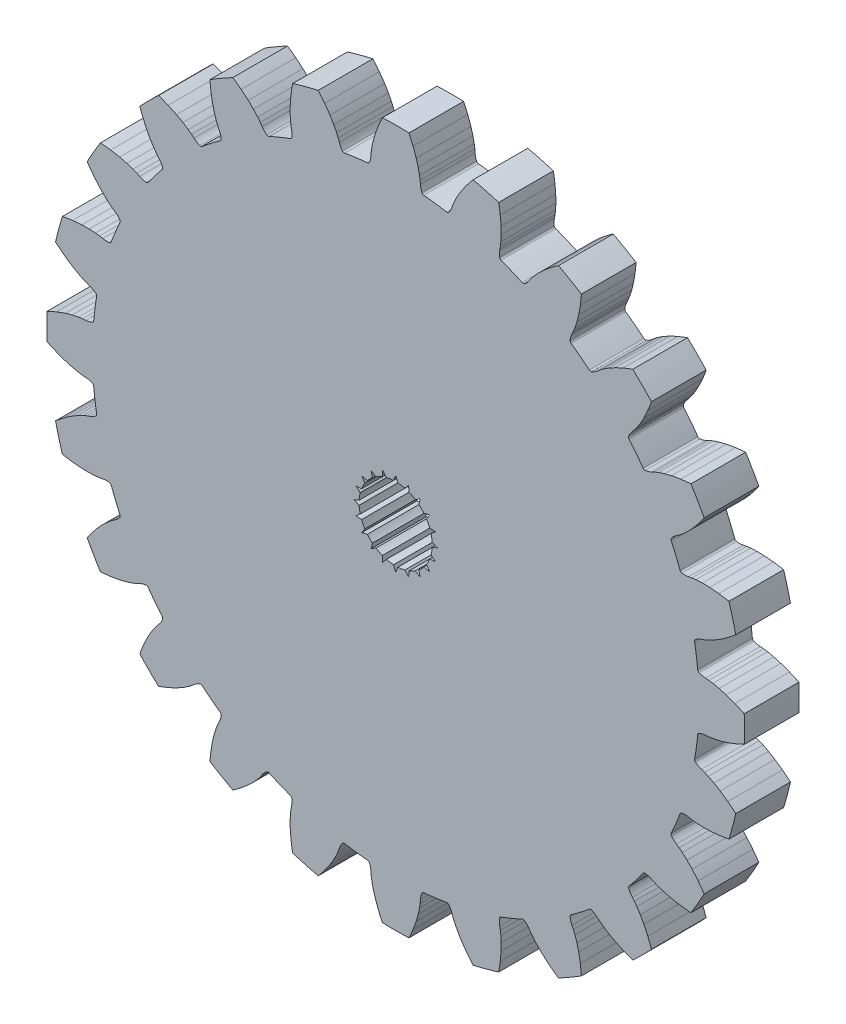
SolidWorks part; units mm, degrees
material "Cast Alloy Steel"
ref_plane "Front Plane" through (0, 0, 0) normal (0, 0, 1) x (1, 0, 0)
ref_plane "Top Plane" through (0, 0, 0) normal (0, 1, 0) x (1, 0, 0)
ref_plane "Right Plane" through (0, 0, 0) normal (1, 0, 0) x (0, 0, -1)
sketch "Model" plane through (0, 0, 0) normal (0, 0, 1) x (1, 0, 0)
  arc A1 (34.9181, -4.5971) -> (35.0673, -3.2696) centre (0, 0) ccw
  arc A2 (35.2278, -3.0481) -> (35.0673, -3.2696) centre (35.3347, -3.2945) ccw
  arc A3 (35.9833, -2.8721) -> (35.2278, -3.0481) centre (36.0877, -5.0299) ccw
  arc A4 (35.9833, -2.8721) -> (36.3636, -2.8405) centre (35.7172, 2.6237) ccw
  arc A5 (36.3636, -2.8405) -> (36.8336, -2.7716) centre (35.3622, 5.6245) ccw
  arc A6 (36.8336, -2.7716) -> (37.5555, -2.6174) centre (35.1043, 7.0963) ccw
  arc A7 (37.5555, -2.6174) -> (38.3737, -2.3829) centre (34.2966, 10.2971) ccw
  arc A8 (38.3737, -2.3829) -> (39.3866, -2.0164) centre (33.8084, 11.8154) ccw
  arc A9 (39.3866, -2.0164) -> (40.4752, -1.5354) centre (32.5769, 14.869) ccw
  arc A10 (40.4752, -1.5354) -> (40.4752, 1.5354) centre (0, 0) ccw
  arc A11 (40.4752, 1.5354) -> (39.3866, 2.0164) centre (32.5769, -14.869) ccw
  arc A12 (39.3866, 2.0164) -> (38.3737, 2.3829) centre (33.8084, -11.8154) ccw
  arc A13 (38.3737, 2.3829) -> (37.5555, 2.6174) centre (34.2966, -10.2971) ccw
  arc A14 (37.5555, 2.6174) -> (36.8336, 2.7716) centre (35.1043, -7.0963) ccw
  arc A15 (36.8336, 2.7716) -> (36.3636, 2.8405) centre (35.3622, -5.6245) ccw
  arc A16 (36.3636, 2.8405) -> (35.9833, 2.8721) centre (35.7172, -2.6237) ccw
  arc A17 (35.2278, 3.0481) -> (35.9833, 2.8721) centre (36.0877, 5.0299) ccw
  arc A18 (35.0673, 3.2696) -> (35.2278, 3.0481) centre (35.3347, 3.2945) ccw
  arc A19 (35.0673, 3.2696) -> (34.7187, 5.9179) centre (0, 0) ccw
  arc A20 (34.8164, 6.1734) -> (34.7187, 5.9179) centre (34.9834, 5.9631) ccw
  arc A21 (35.5005, 6.5389) -> (34.8164, 6.1734) centre (36.1599, 4.4817) ccw
  arc A22 (35.5005, 6.5389) -> (35.8597, 6.6679) centre (33.8211, 11.7785) ccw
  arc A23 (35.8597, 6.6679) -> (36.2958, 6.8561) centre (32.7015, 14.5853) ccw
  arc A24 (36.2958, 6.8561) -> (36.9533, 7.1918) centre (32.0715, 15.9402) ccw
  arc A25 (36.9533, 7.1918) -> (37.6829, 7.6301) centre (30.4629, 18.8229) ccw
  arc A26 (37.6829, 7.6301) -> (38.5664, 8.2463) centre (29.5984, 20.1631) ccw
  arc A27 (38.5664, 8.2463) -> (39.4934, 8.9927) centre (27.6185, 22.7939) ccw
  arc A28 (39.4934, 8.9927) -> (38.6987, 11.9589) centre (0, 0) ccw
  arc A29 (38.6987, 11.9589) -> (37.5227, 12.1417) centre (35.3153, -5.9309) ccw
  arc A30 (37.5227, 12.1417) -> (36.4494, 12.2336) centre (35.7145, -2.6625) ccw
  arc A31 (36.4494, 12.2336) -> (35.5984, 12.2483) centre (35.7931, -1.0696) ccw
  arc A32 (35.5984, 12.2483) -> (34.8612, 12.2104) centre (35.7448, 2.2311) ccw
  arc A33 (34.8612, 12.2104) -> (34.3894, 12.1553) centre (35.613, 3.7195) ccw
  arc A34 (34.3894, 12.1553) -> (34.0138, 12.0874) centre (35.1792, 6.71) ccw
  arc A35 (33.2386, 12.0619) -> (34.0138, 12.0874) centre (33.5562, 14.1987) ccw
  arc A36 (33.0262, 12.2343) -> (33.2386, 12.0619) centre (33.2781, 12.3275) ccw
  arc A37 (33.0262, 12.2343) -> (32.004, 14.7021) centre (0, 0) ccw
  arc A38 (32.0323, 14.9742) -> (32.004, 14.7021) centre (32.248, 14.8142) ccw
  arc A39 (32.5985, 15.5043) -> (32.0323, 14.9742) centre (33.7678, 13.6878) ccw
  arc A40 (32.5985, 15.5043) -> (32.912, 15.7219) centre (29.6202, 20.1308) ccw
  arc A41 (32.912, 15.7219) -> (33.2846, 16.0165) centre (27.8123, 22.5521) ccw
  arc A42 (33.2846, 16.0165) -> (33.8327, 16.511) centre (26.853, 23.6978) ccw
  arc A43 (33.8327, 16.511) -> (34.4241, 17.1232) centre (24.5532, 26.0659) ccw
  arc A44 (34.4241, 17.1232) -> (35.118, 17.9471) centre (23.3712, 27.1366) ccw
  arc A45 (35.118, 17.9471) -> (35.8203, 18.9079) centre (20.7779, 29.1654) ccw
  arc A46 (35.8203, 18.9079) -> (34.2849, 21.5673) centre (0, 0) ccw
  arc A47 (34.2849, 21.5673) -> (33.1016, 21.4395) centre (35.647, 3.4115) ccw
  arc A48 (33.1016, 21.4395) -> (32.0412, 21.2505) centre (35.1866, 6.6718) ccw
  arc A49 (32.0412, 21.2505) -> (31.2153, 21.0445) centre (34.8503, 8.2307) ccw
  arc A50 (31.2153, 21.0445) -> (30.513, 20.817) centre (33.9494, 11.4065) ccw
  arc A51 (30.513, 20.817) -> (30.0715, 20.6417) centre (33.4369, 12.8101) ccw
  arc A52 (30.0715, 20.6417) -> (29.7263, 20.479) centre (32.2438, 15.5865) ccw
  arc A53 (28.9841, 20.2537) -> (29.7263, 20.479) centre (28.7379, 22.3999) ccw
  arc A54 (28.7344, 20.3652) -> (28.9841, 20.2537) centre (28.9535, 20.5205) ccw
  arc A55 (28.7344, 20.3652) -> (27.1083, 22.4844) centre (0, 0) ccw
  arc A56 (27.0652, 22.7545) -> (27.1083, 22.4844) centre (27.315, 22.6559) ccw
  arc A57 (27.4749, 23.4131) -> (27.0652, 22.7545) centre (29.0746, 21.9612) ccw
  arc A58 (27.4749, 23.4131) -> (27.7215, 23.7044) centre (23.4007, 27.1111) ccw
  arc A59 (27.7215, 23.7044) -> (28.0051, 24.0855) centre (21.0277, 28.982) ccw
  arc A60 (28.0051, 24.0855) -> (28.4066, 24.7049) centre (19.8046, 29.8404) ccw
  arc A61 (28.4066, 24.7049) -> (28.8193, 25.4493) centre (16.9702, 31.5325) ccw
  arc A62 (28.8193, 25.4493) -> (29.2763, 26.4247) centre (15.5514, 32.2609) ccw
  arc A63 (29.2763, 26.4247) -> (29.706, 27.5346) centre (12.5214, 33.5494) ccw
  arc A64 (29.706, 27.5346) -> (27.5346, 29.706) centre (0, 0) ccw
  arc A65 (27.5346, 29.706) -> (26.4247, 29.2763) centre (33.5494, 12.5214) ccw
  arc A66 (26.4247, 29.2763) -> (25.4493, 28.8193) centre (32.2609, 15.5514) ccw
  arc A67 (25.4493, 28.8193) -> (24.7049, 28.4066) centre (31.5325, 16.9702) ccw
  arc A68 (24.7049, 28.4066) -> (24.0855, 28.0051) centre (29.8404, 19.8046) ccw
  arc A69 (24.0855, 28.0051) -> (23.7044, 27.7215) centre (28.982, 21.0277) ccw
  arc A70 (23.7044, 27.7215) -> (23.4131, 27.4749) centre (27.1111, 23.4007) ccw
  arc A71 (22.7545, 27.0652) -> (23.4131, 27.4749) centre (21.9612, 29.0746) ccw
  arc A72 (22.4844, 27.1083) -> (22.7545, 27.0652) centre (22.6559, 27.315) ccw
  arc A73 (22.4844, 27.1083) -> (20.3652, 28.7344) centre (0, 0) ccw
  arc A74 (20.2537, 28.9841) -> (20.3652, 28.7344) centre (20.5205, 28.9535) ccw
  arc A75 (20.479, 29.7263) -> (20.2537, 28.9841) centre (22.3999, 28.7379) ccw
  arc A76 (20.479, 29.7263) -> (20.6417, 30.0715) centre (15.5865, 32.2438) ccw
  arc A77 (20.6417, 30.0715) -> (20.817, 30.513) centre (12.8101, 33.4369) ccw
  arc A78 (20.817, 30.513) -> (21.0445, 31.2153) centre (11.4065, 33.9494) ccw
  arc A79 (21.0445, 31.2153) -> (21.2505, 32.0412) centre (8.2307, 34.8503) ccw
  arc A80 (21.2505, 32.0412) -> (21.4395, 33.1016) centre (6.6718, 35.1866) ccw
  arc A81 (21.4395, 33.1016) -> (21.5673, 34.2849) centre (3.4115, 35.647) ccw
  arc A82 (21.5673, 34.2849) -> (18.9079, 35.8203) centre (0, 0) ccw
  arc A83 (18.9079, 35.8203) -> (17.9471, 35.118) centre (29.1654, 20.7779) ccw
  arc A84 (17.9471, 35.118) -> (17.1232, 34.4241) centre (27.1366, 23.3712) ccw
  arc A85 (17.1232, 34.4241) -> (16.511, 33.8327) centre (26.0659, 24.5532) ccw
  arc A86 (16.511, 33.8327) -> (16.0165, 33.2846) centre (23.6978, 26.853) ccw
  arc A87 (16.0165, 33.2846) -> (15.7219, 32.912) centre (22.5521, 27.8123) ccw
  arc A88 (15.7219, 32.912) -> (15.5043, 32.5985) centre (20.1308, 29.6202) ccw
  arc A89 (14.9742, 32.0323) -> (15.5043, 32.5985) centre (13.6878, 33.7678) ccw
  arc A90 (14.7021, 32.004) -> (14.9742, 32.0323) centre (14.8142, 32.248) ccw
  arc A91 (14.7021, 32.004) -> (12.2343, 33.0262) centre (0, 0) ccw
  arc A92 (12.0619, 33.2386) -> (12.2343, 33.0262) centre (12.3275, 33.2781) ccw
  arc A93 (12.0874, 34.0138) -> (12.0619, 33.2386) centre (14.1987, 33.5562) ccw
  arc A94 (12.0874, 34.0138) -> (12.1553, 34.3894) centre (6.71, 35.1792) ccw
  arc A95 (12.1553, 34.3894) -> (12.2104, 34.8612) centre (3.7195, 35.613) ccw
  arc A96 (12.2104, 34.8612) -> (12.2483, 35.5984) centre (2.2311, 35.7448) ccw
  arc A97 (12.2483, 35.5984) -> (12.2336, 36.4494) centre (-1.0696, 35.7931) ccw
  arc A98 (12.2336, 36.4494) -> (12.1417, 37.5227) centre (-2.6625, 35.7145) ccw
  arc A99 (12.1417, 37.5227) -> (11.9589, 38.6987) centre (-5.9309, 35.3153) ccw
  arc A100 (11.9589, 38.6987) -> (8.9927, 39.4934) centre (0, 0) ccw
  arc A101 (8.9927, 39.4934) -> (8.2463, 38.5664) centre (22.7939, 27.6185) ccw
  arc A102 (8.2463, 38.5664) -> (7.6301, 37.6829) centre (20.1631, 29.5984) ccw
  arc A103 (7.6301, 37.6829) -> (7.1918, 36.9533) centre (18.8229, 30.4629) ccw
  arc A104 (7.1918, 36.9533) -> (6.8561, 36.2958) centre (15.9402, 32.0715) ccw
  arc A105 (6.8561, 36.2958) -> (6.6679, 35.8597) centre (14.5853, 32.7015) ccw
  arc A106 (6.6679, 35.8597) -> (6.5389, 35.5005) centre (11.7785, 33.8211) ccw
  arc A107 (6.1734, 34.8164) -> (6.5389, 35.5005) centre (4.4817, 36.1599) ccw
  arc A108 (5.9179, 34.7187) -> (6.1734, 34.8164) centre (5.9631, 34.9834) ccw
  arc A109 (5.9179, 34.7187) -> (3.2696, 35.0673) centre (0, 0) ccw
  arc A110 (3.0481, 35.2278) -> (3.2696, 35.0673) centre (3.2945, 35.3347) ccw
  arc A111 (2.8721, 35.9833) -> (3.0481, 35.2278) centre (5.0299, 36.0877) ccw
  arc A112 (2.8721, 35.9833) -> (2.8405, 36.3636) centre (-2.6237, 35.7172) ccw
  arc A113 (2.8405, 36.3636) -> (2.7716, 36.8336) centre (-5.6245, 35.3622) ccw
  arc A114 (2.7716, 36.8336) -> (2.6174, 37.5555) centre (-7.0963, 35.1043) ccw
  arc A115 (2.6174, 37.5555) -> (2.3829, 38.3737) centre (-10.2971, 34.2966) ccw
  arc A116 (2.3829, 38.3737) -> (2.0164, 39.3866) centre (-11.8154, 33.8084) ccw
  arc A117 (2.0164, 39.3866) -> (1.5354, 40.4752) centre (-14.869, 32.5769) ccw
  arc A118 (1.5354, 40.4752) -> (-1.5354, 40.4752) centre (0, 0) ccw
  arc A119 (-1.5354, 40.4752) -> (-2.0164, 39.3866) centre (14.869, 32.5769) ccw
  arc A120 (-2.0164, 39.3866) -> (-2.3829, 38.3737) centre (11.8154, 33.8084) ccw
  arc A121 (-2.3829, 38.3737) -> (-2.6174, 37.5555) centre (10.2971, 34.2966) ccw
  arc A122 (-2.6174, 37.5555) -> (-2.7716, 36.8336) centre (7.0963, 35.1043) ccw
  arc A123 (-2.7716, 36.8336) -> (-2.8405, 36.3636) centre (5.6245, 35.3622) ccw
  arc A124 (-2.8405, 36.3636) -> (-2.8721, 35.9833) centre (2.6237, 35.7172) ccw
  arc A125 (-3.0481, 35.2278) -> (-2.8721, 35.9833) centre (-5.0299, 36.0877) ccw
  arc A126 (-3.2696, 35.0673) -> (-3.0481, 35.2278) centre (-3.2945, 35.3347) ccw
  arc A127 (-3.2696, 35.0673) -> (-5.9179, 34.7187) centre (0, 0) ccw
  arc A128 (-6.1734, 34.8164) -> (-5.9179, 34.7187) centre (-5.9631, 34.9834) ccw
  arc A129 (-6.5389, 35.5005) -> (-6.1734, 34.8164) centre (-4.4817, 36.1599) ccw
  arc A130 (-6.5389, 35.5005) -> (-6.6679, 35.8597) centre (-11.7785, 33.8211) ccw
  arc A131 (-6.6679, 35.8597) -> (-6.8561, 36.2958) centre (-14.5853, 32.7015) ccw
  arc A132 (-6.8561, 36.2958) -> (-7.1918, 36.9533) centre (-15.9402, 32.0715) ccw
  arc A133 (-7.1918, 36.9533) -> (-7.6301, 37.6829) centre (-18.8229, 30.4629) ccw
  arc A134 (-7.6301, 37.6829) -> (-8.2463, 38.5664) centre (-20.1631, 29.5984) ccw
  arc A135 (-8.2463, 38.5664) -> (-8.9927, 39.4934) centre (-22.7939, 27.6185) ccw
  arc A136 (-8.9927, 39.4934) -> (-11.9589, 38.6987) centre (0, 0) ccw
  arc A137 (-11.9589, 38.6987) -> (-12.1417, 37.5227) centre (5.9309, 35.3153) ccw
  arc A138 (-12.1417, 37.5227) -> (-12.2336, 36.4494) centre (2.6625, 35.7145) ccw
  arc A139 (-12.2336, 36.4494) -> (-12.2483, 35.5984) centre (1.0696, 35.7931) ccw
  arc A140 (-12.2483, 35.5984) -> (-12.2104, 34.8612) centre (-2.2311, 35.7448) ccw
  arc A141 (-12.2104, 34.8612) -> (-12.1553, 34.3894) centre (-3.7195, 35.613) ccw
  arc A142 (-12.1553, 34.3894) -> (-12.0874, 34.0138) centre (-6.71, 35.1792) ccw
  arc A143 (-12.0619, 33.2386) -> (-12.0874, 34.0138) centre (-14.1987, 33.5562) ccw
  arc A144 (-12.2343, 33.0262) -> (-12.0619, 33.2386) centre (-12.3275, 33.2781) ccw
  arc A145 (-12.2343, 33.0262) -> (-14.7021, 32.004) centre (0, 0) ccw
  arc A146 (-14.9742, 32.0323) -> (-14.7021, 32.004) centre (-14.8142, 32.248) ccw
  arc A147 (-15.5043, 32.5985) -> (-14.9742, 32.0323) centre (-13.6878, 33.7678) ccw
  arc A148 (-15.5043, 32.5985) -> (-15.7219, 32.912) centre (-20.1308, 29.6202) ccw
  arc A149 (-15.7219, 32.912) -> (-16.0165, 33.2846) centre (-22.5521, 27.8123) ccw
  arc A150 (-16.0165, 33.2846) -> (-16.511, 33.8327) centre (-23.6978, 26.853) ccw
  arc A151 (-16.511, 33.8327) -> (-17.1232, 34.4241) centre (-26.0659, 24.5532) ccw
  arc A152 (-17.1232, 34.4241) -> (-17.9471, 35.118) centre (-27.1366, 23.3712) ccw
  arc A153 (-17.9471, 35.118) -> (-18.9079, 35.8203) centre (-29.1654, 20.7779) ccw
  arc A154 (-18.9079, 35.8203) -> (-21.5673, 34.2849) centre (0, 0) ccw
  arc A155 (-21.5673, 34.2849) -> (-21.4395, 33.1016) centre (-3.4115, 35.647) ccw
  arc A156 (-21.4395, 33.1016) -> (-21.2505, 32.0412) centre (-6.6718, 35.1866) ccw
  arc A157 (-21.2505, 32.0412) -> (-21.0445, 31.2153) centre (-8.2307, 34.8503) ccw
  arc A158 (-21.0445, 31.2153) -> (-20.817, 30.513) centre (-11.4065, 33.9494) ccw
  arc A159 (-20.817, 30.513) -> (-20.6417, 30.0715) centre (-12.8101, 33.4369) ccw
  arc A160 (-20.6417, 30.0715) -> (-20.479, 29.7263) centre (-15.5865, 32.2438) ccw
  arc A161 (-20.2537, 28.9841) -> (-20.479, 29.7263) centre (-22.3999, 28.7379) ccw
  arc A162 (-20.3652, 28.7344) -> (-20.2537, 28.9841) centre (-20.5205, 28.9535) ccw
  arc A163 (-20.3652, 28.7344) -> (-22.4844, 27.1083) centre (0, 0) ccw
  arc A164 (-22.7545, 27.0652) -> (-22.4844, 27.1083) centre (-22.6559, 27.315) ccw
  arc A165 (-23.4131, 27.4749) -> (-22.7545, 27.0652) centre (-21.9612, 29.0746) ccw
  arc A166 (-23.4131, 27.4749) -> (-23.7044, 27.7215) centre (-27.1111, 23.4007) ccw
  arc A167 (-23.7044, 27.7215) -> (-24.0855, 28.0051) centre (-28.982, 21.0277) ccw
  arc A168 (-24.0855, 28.0051) -> (-24.7049, 28.4066) centre (-29.8404, 19.8046) ccw
  arc A169 (-24.7049, 28.4066) -> (-25.4493, 28.8193) centre (-31.5325, 16.9702) ccw
  arc A170 (-25.4493, 28.8193) -> (-26.4247, 29.2763) centre (-32.2609, 15.5514) ccw
  arc A171 (-26.4247, 29.2763) -> (-27.5346, 29.706) centre (-33.5494, 12.5214) ccw
  arc A172 (-27.5346, 29.706) -> (-29.706, 27.5346) centre (0, 0) ccw
  arc A173 (-29.706, 27.5346) -> (-29.2763, 26.4247) centre (-12.5214, 33.5494) ccw
  arc A174 (-29.2763, 26.4247) -> (-28.8193, 25.4493) centre (-15.5514, 32.2609) ccw
  arc A175 (-28.8193, 25.4493) -> (-28.4066, 24.7049) centre (-16.9702, 31.5325) ccw
  arc A176 (-28.4066, 24.7049) -> (-28.0051, 24.0855) centre (-19.8046, 29.8404) ccw
  arc A177 (-28.0051, 24.0855) -> (-27.7215, 23.7044) centre (-21.0277, 28.982) ccw
  arc A178 (-27.7215, 23.7044) -> (-27.4749, 23.4131) centre (-23.4007, 27.1111) ccw
  arc A179 (-27.0652, 22.7545) -> (-27.4749, 23.4131) centre (-29.0746, 21.9612) ccw
  arc A180 (-27.1083, 22.4844) -> (-27.0652, 22.7545) centre (-27.315, 22.6559) ccw
  arc A181 (-27.1083, 22.4844) -> (-28.7344, 20.3652) centre (0, 0) ccw
  arc A182 (-28.9841, 20.2537) -> (-28.7344, 20.3652) centre (-28.9535, 20.5205) ccw
  arc A183 (-29.7263, 20.479) -> (-28.9841, 20.2537) centre (-28.7379, 22.3999) ccw
  arc A184 (-29.7263, 20.479) -> (-30.0715, 20.6417) centre (-32.2438, 15.5865) ccw
  arc A185 (-30.0715, 20.6417) -> (-30.513, 20.817) centre (-33.4369, 12.8101) ccw
  arc A186 (-30.513, 20.817) -> (-31.2153, 21.0445) centre (-33.9494, 11.4065) ccw
  arc A187 (-31.2153, 21.0445) -> (-32.0412, 21.2505) centre (-34.8503, 8.2307) ccw
  arc A188 (-32.0412, 21.2505) -> (-33.1016, 21.4395) centre (-35.1866, 6.6718) ccw
  arc A189 (-33.1016, 21.4395) -> (-34.2849, 21.5673) centre (-35.647, 3.4115) ccw
  arc A190 (-34.2849, 21.5673) -> (-35.8203, 18.9079) centre (0, 0) ccw
  arc A191 (-35.8203, 18.9079) -> (-35.118, 17.9471) centre (-20.7779, 29.1654) ccw
  arc A192 (-35.118, 17.9471) -> (-34.4241, 17.1232) centre (-23.3712, 27.1366) ccw
  arc A193 (-34.4241, 17.1232) -> (-33.8327, 16.511) centre (-24.5532, 26.0659) ccw
  arc A194 (-33.8327, 16.511) -> (-33.2846, 16.0165) centre (-26.853, 23.6978) ccw
  arc A195 (-33.2846, 16.0165) -> (-32.912, 15.7219) centre (-27.8123, 22.5521) ccw
  arc A196 (-32.912, 15.7219) -> (-32.5985, 15.5043) centre (-29.6202, 20.1308) ccw
  arc A197 (-32.0323, 14.9742) -> (-32.5985, 15.5043) centre (-33.7678, 13.6878) ccw
  arc A198 (-32.004, 14.7021) -> (-32.0323, 14.9742) centre (-32.248, 14.8142) ccw
  arc A199 (-32.004, 14.7021) -> (-33.0262, 12.2343) centre (0, 0) ccw
  arc A200 (-33.2386, 12.0619) -> (-33.0262, 12.2343) centre (-33.2781, 12.3275) ccw
  arc A201 (-34.0138, 12.0874) -> (-33.2386, 12.0619) centre (-33.5562, 14.1987) ccw
  arc A202 (-34.0138, 12.0874) -> (-34.3894, 12.1553) centre (-35.1792, 6.71) ccw
  arc A203 (-34.3894, 12.1553) -> (-34.8612, 12.2104) centre (-35.613, 3.7195) ccw
  arc A204 (-34.8612, 12.2104) -> (-35.5984, 12.2483) centre (-35.7448, 2.2311) ccw
  arc A205 (-35.5984, 12.2483) -> (-36.4494, 12.2336) centre (-35.7931, -1.0696) ccw
  arc A206 (-36.4494, 12.2336) -> (-37.5227, 12.1417) centre (-35.7145, -2.6625) ccw
  arc A207 (-37.5227, 12.1417) -> (-38.6987, 11.9589) centre (-35.3153, -5.9309) ccw
  arc A208 (-38.6987, 11.9589) -> (-39.4934, 8.9927) centre (0, 0) ccw
  arc A209 (-39.4934, 8.9927) -> (-38.5664, 8.2463) centre (-27.6185, 22.7939) ccw
  arc A210 (-38.5664, 8.2463) -> (-37.6829, 7.6301) centre (-29.5984, 20.1631) ccw
  arc A211 (-37.6829, 7.6301) -> (-36.9533, 7.1918) centre (-30.4629, 18.8229) ccw
  arc A212 (-36.9533, 7.1918) -> (-36.2958, 6.8561) centre (-32.0715, 15.9402) ccw
  arc A213 (-36.2958, 6.8561) -> (-35.8597, 6.6679) centre (-32.7015, 14.5853) ccw
  arc A214 (-35.8597, 6.6679) -> (-35.5005, 6.5389) centre (-33.8211, 11.7785) ccw
  arc A215 (-34.8164, 6.1734) -> (-35.5005, 6.5389) centre (-36.1599, 4.4817) ccw
  arc A216 (-34.7187, 5.9179) -> (-34.8164, 6.1734) centre (-34.9834, 5.9631) ccw
  arc A217 (-34.7187, 5.9179) -> (-35.0673, 3.2696) centre (0, 0) ccw
  arc A218 (-35.2278, 3.0481) -> (-35.0673, 3.2696) centre (-35.3347, 3.2945) ccw
  arc A219 (-35.9833, 2.8721) -> (-35.2278, 3.0481) centre (-36.0877, 5.0299) ccw
  arc A220 (-35.9833, 2.8721) -> (-36.3636, 2.8405) centre (-35.7172, -2.6237) ccw
  arc A221 (-36.3636, 2.8405) -> (-36.8336, 2.7716) centre (-35.3622, -5.6245) ccw
  arc A222 (-36.8336, 2.7716) -> (-37.5555, 2.6174) centre (-35.1043, -7.0963) ccw
  arc A223 (-37.5555, 2.6174) -> (-38.3737, 2.3829) centre (-34.2966, -10.2971) ccw
  arc A224 (-38.3737, 2.3829) -> (-39.3866, 2.0164) centre (-33.8084, -11.8154) ccw
  arc A225 (-39.3866, 2.0164) -> (-40.4752, 1.5354) centre (-32.5769, -14.869) ccw
  arc A226 (-40.4752, 1.5354) -> (-40.4752, -1.5354) centre (0, 0) ccw
  arc A227 (-40.4752, -1.5354) -> (-39.3866, -2.0164) centre (-32.5769, 14.869) ccw
  arc A228 (-39.3866, -2.0164) -> (-38.3737, -2.3829) centre (-33.8084, 11.8154) ccw
  arc A229 (-38.3737, -2.3829) -> (-37.5555, -2.6174) centre (-34.2966, 10.2971) ccw
  arc A230 (-37.5555, -2.6174) -> (-36.8336, -2.7716) centre (-35.1043, 7.0963) ccw
  arc A231 (-36.8336, -2.7716) -> (-36.3636, -2.8405) centre (-35.3622, 5.6245) ccw
  arc A232 (-36.3636, -2.8405) -> (-35.9833, -2.8721) centre (-35.7172, 2.6237) ccw
  arc A233 (-35.2278, -3.0481) -> (-35.9833, -2.8721) centre (-36.0877, -5.0299) ccw
  arc A234 (-35.0673, -3.2696) -> (-35.2278, -3.0481) centre (-35.3347, -3.2945) ccw
  arc A235 (-35.0673, -3.2696) -> (-34.7187, -5.9179) centre (0, 0) ccw
  arc A236 (-34.8164, -6.1734) -> (-34.7187, -5.9179) centre (-34.9834, -5.9631) ccw
  arc A237 (-35.5005, -6.5389) -> (-34.8164, -6.1734) centre (-36.1599, -4.4817) ccw
  arc A238 (-35.5005, -6.5389) -> (-35.8597, -6.6679) centre (-33.8211, -11.7785) ccw
  arc A239 (-35.8597, -6.6679) -> (-36.2958, -6.8561) centre (-32.7015, -14.5853) ccw
  arc A240 (-36.2958, -6.8561) -> (-36.9533, -7.1918) centre (-32.0715, -15.9402) ccw
  arc A241 (-36.9533, -7.1918) -> (-37.6829, -7.6301) centre (-30.4629, -18.8229) ccw
  arc A242 (-37.6829, -7.6301) -> (-38.5664, -8.2463) centre (-29.5984, -20.1631) ccw
  arc A243 (-38.5664, -8.2463) -> (-39.4934, -8.9927) centre (-27.6185, -22.7939) ccw
  arc A244 (-39.4934, -8.9927) -> (-38.6987, -11.9589) centre (0, 0) ccw
  arc A245 (-38.6987, -11.9589) -> (-37.5227, -12.1417) centre (-35.3153, 5.9309) ccw
  arc A246 (-37.5227, -12.1417) -> (-36.4494, -12.2336) centre (-35.7145, 2.6625) ccw
  arc A247 (-36.4494, -12.2336) -> (-35.5984, -12.2483) centre (-35.7931, 1.0696) ccw
  arc A248 (-35.5984, -12.2483) -> (-34.8612, -12.2104) centre (-35.7448, -2.2311) ccw
  arc A249 (-34.8612, -12.2104) -> (-34.3894, -12.1553) centre (-35.613, -3.7195) ccw
  arc A250 (-34.3894, -12.1553) -> (-34.0138, -12.0874) centre (-35.1792, -6.71) ccw
  arc A251 (-33.2386, -12.0619) -> (-34.0138, -12.0874) centre (-33.5562, -14.1987) ccw
  arc A252 (-33.0262, -12.2343) -> (-33.2386, -12.0619) centre (-33.2781, -12.3275) ccw
  arc A253 (-33.0262, -12.2343) -> (-32.004, -14.7021) centre (0, 0) ccw
  arc A254 (-32.0323, -14.9742) -> (-32.004, -14.7021) centre (-32.248, -14.8142) ccw
  arc A255 (-32.5985, -15.5043) -> (-32.0323, -14.9742) centre (-33.7678, -13.6878) ccw
  arc A256 (-32.5985, -15.5043) -> (-32.912, -15.7219) centre (-29.6202, -20.1308) ccw
  arc A257 (-32.912, -15.7219) -> (-33.2846, -16.0165) centre (-27.8123, -22.5521) ccw
  arc A258 (-33.2846, -16.0165) -> (-33.8327, -16.511) centre (-26.853, -23.6978) ccw
  arc A259 (-33.8327, -16.511) -> (-34.4241, -17.1232) centre (-24.5532, -26.0659) ccw
  arc A260 (-34.4241, -17.1232) -> (-35.118, -17.9471) centre (-23.3712, -27.1366) ccw
  arc A261 (-35.118, -17.9471) -> (-35.8203, -18.9079) centre (-20.7779, -29.1654) ccw
  arc A262 (-35.8203, -18.9079) -> (-34.2849, -21.5673) centre (0, 0) ccw
  arc A263 (-34.2849, -21.5673) -> (-33.1016, -21.4395) centre (-35.647, -3.4115) ccw
  arc A264 (-33.1016, -21.4395) -> (-32.0412, -21.2505) centre (-35.1866, -6.6718) ccw
  arc A265 (-32.0412, -21.2505) -> (-31.2153, -21.0445) centre (-34.8503, -8.2307) ccw
  arc A266 (-31.2153, -21.0445) -> (-30.513, -20.817) centre (-33.9494, -11.4065) ccw
  arc A267 (-30.513, -20.817) -> (-30.0715, -20.6417) centre (-33.4369, -12.8101) ccw
  arc A268 (-30.0715, -20.6417) -> (-29.7263, -20.479) centre (-32.2438, -15.5865) ccw
  arc A269 (-28.9841, -20.2537) -> (-29.7263, -20.479) centre (-28.7379, -22.3999) ccw
  arc A270 (-28.7344, -20.3652) -> (-28.9841, -20.2537) centre (-28.9535, -20.5205) ccw
  arc A271 (-28.7344, -20.3652) -> (-27.1083, -22.4844) centre (0, 0) ccw
  arc A272 (-27.0652, -22.7545) -> (-27.1083, -22.4844) centre (-27.315, -22.6559) ccw
  arc A273 (-27.4749, -23.4131) -> (-27.0652, -22.7545) centre (-29.0746, -21.9612) ccw
  arc A274 (-27.4749, -23.4131) -> (-27.7215, -23.7044) centre (-23.4007, -27.1111) ccw
  arc A275 (-27.7215, -23.7044) -> (-28.0051, -24.0855) centre (-21.0277, -28.982) ccw
  arc A276 (-28.0051, -24.0855) -> (-28.4066, -24.7049) centre (-19.8046, -29.8404) ccw
  arc A277 (-28.4066, -24.7049) -> (-28.8193, -25.4493) centre (-16.9702, -31.5325) ccw
  arc A278 (-28.8193, -25.4493) -> (-29.2763, -26.4247) centre (-15.5514, -32.2609) ccw
  arc A279 (-29.2763, -26.4247) -> (-29.706, -27.5346) centre (-12.5214, -33.5494) ccw
  arc A280 (-29.706, -27.5346) -> (-27.5346, -29.706) centre (0, 0) ccw
  arc A281 (-27.5346, -29.706) -> (-26.4247, -29.2763) centre (-33.5494, -12.5214) ccw
  arc A282 (-26.4247, -29.2763) -> (-25.4493, -28.8193) centre (-32.2609, -15.5514) ccw
  arc A283 (-25.4493, -28.8193) -> (-24.7049, -28.4066) centre (-31.5325, -16.9702) ccw
  arc A284 (-24.7049, -28.4066) -> (-24.0855, -28.0051) centre (-29.8404, -19.8046) ccw
  arc A285 (-24.0855, -28.0051) -> (-23.7044, -27.7215) centre (-28.982, -21.0277) ccw
  arc A286 (-23.7044, -27.7215) -> (-23.4131, -27.4749) centre (-27.1111, -23.4007) ccw
  arc A287 (-22.7545, -27.0652) -> (-23.4131, -27.4749) centre (-21.9612, -29.0746) ccw
  arc A288 (-22.4844, -27.1083) -> (-22.7545, -27.0652) centre (-22.6559, -27.315) ccw
  arc A289 (-22.4844, -27.1083) -> (-20.3652, -28.7344) centre (0, 0) ccw
  arc A290 (-20.2537, -28.9841) -> (-20.3652, -28.7344) centre (-20.5205, -28.9535) ccw
  arc A291 (-20.479, -29.7263) -> (-20.2537, -28.9841) centre (-22.3999, -28.7379) ccw
  arc A292 (-20.479, -29.7263) -> (-20.6417, -30.0715) centre (-15.5865, -32.2438) ccw
  arc A293 (-20.6417, -30.0715) -> (-20.817, -30.513) centre (-12.8101, -33.4369) ccw
  arc A294 (-20.817, -30.513) -> (-21.0445, -31.2153) centre (-11.4065, -33.9494) ccw
  arc A295 (-21.0445, -31.2153) -> (-21.2505, -32.0412) centre (-8.2307, -34.8503) ccw
  arc A296 (-21.2505, -32.0412) -> (-21.4395, -33.1016) centre (-6.6718, -35.1866) ccw
  arc A297 (-21.4395, -33.1016) -> (-21.5673, -34.2849) centre (-3.4115, -35.647) ccw
  arc A298 (-21.5673, -34.2849) -> (-18.9079, -35.8203) centre (0, 0) ccw
  arc A299 (-18.9079, -35.8203) -> (-17.9471, -35.118) centre (-29.1654, -20.7779) ccw
  arc A300 (-17.9471, -35.118) -> (-17.1232, -34.4241) centre (-27.1366, -23.3712) ccw
  arc A301 (-17.1232, -34.4241) -> (-16.511, -33.8327) centre (-26.0659, -24.5532) ccw
  arc A302 (-16.511, -33.8327) -> (-16.0165, -33.2846) centre (-23.6978, -26.853) ccw
  arc A303 (-16.0165, -33.2846) -> (-15.7219, -32.912) centre (-22.5521, -27.8123) ccw
  arc A304 (-15.7219, -32.912) -> (-15.5043, -32.5985) centre (-20.1308, -29.6202) ccw
  arc A305 (-14.9742, -32.0323) -> (-15.5043, -32.5985) centre (-13.6878, -33.7678) ccw
  arc A306 (-14.7021, -32.004) -> (-14.9742, -32.0323) centre (-14.8142, -32.248) ccw
  arc A307 (-14.7021, -32.004) -> (-12.2343, -33.0262) centre (0, 0) ccw
  arc A308 (-12.0619, -33.2386) -> (-12.2343, -33.0262) centre (-12.3275, -33.2781) ccw
  arc A309 (-12.0874, -34.0138) -> (-12.0619, -33.2386) centre (-14.1987, -33.5562) ccw
  arc A310 (-12.0874, -34.0138) -> (-12.1553, -34.3894) centre (-6.71, -35.1792) ccw
  arc A311 (-12.1553, -34.3894) -> (-12.2104, -34.8612) centre (-3.7195, -35.613) ccw
  arc A312 (-12.2104, -34.8612) -> (-12.2483, -35.5984) centre (-2.2311, -35.7448) ccw
  arc A313 (-12.2483, -35.5984) -> (-12.2336, -36.4494) centre (1.0696, -35.7931) ccw
  arc A314 (-12.2336, -36.4494) -> (-12.1417, -37.5227) centre (2.6625, -35.7145) ccw
  arc A315 (-12.1417, -37.5227) -> (-11.9589, -38.6987) centre (5.9309, -35.3153) ccw
  arc A316 (-11.9589, -38.6987) -> (-8.9927, -39.4934) centre (0, 0) ccw
  arc A317 (-8.9927, -39.4934) -> (-8.2463, -38.5664) centre (-22.7939, -27.6185) ccw
  arc A318 (-8.2463, -38.5664) -> (-7.6301, -37.6829) centre (-20.1631, -29.5984) ccw
  arc A319 (-7.6301, -37.6829) -> (-7.1918, -36.9533) centre (-18.8229, -30.4629) ccw
  arc A320 (-7.1918, -36.9533) -> (-6.8561, -36.2958) centre (-15.9402, -32.0715) ccw
  arc A321 (-6.8561, -36.2958) -> (-6.6679, -35.8597) centre (-14.5853, -32.7015) ccw
  arc A322 (-6.6679, -35.8597) -> (-6.5389, -35.5005) centre (-11.7785, -33.8211) ccw
  arc A323 (-6.1734, -34.8164) -> (-6.5389, -35.5005) centre (-4.4817, -36.1599) ccw
  arc A324 (-5.9179, -34.7187) -> (-6.1734, -34.8164) centre (-5.9631, -34.9834) ccw
  arc A325 (-5.9179, -34.7187) -> (-3.2696, -35.0673) centre (0, 0) ccw
  arc A326 (-3.0481, -35.2278) -> (-3.2696, -35.0673) centre (-3.2945, -35.3347) ccw
  arc A327 (-2.8721, -35.9833) -> (-3.0481, -35.2278) centre (-5.0299, -36.0877) ccw
  arc A328 (-2.8721, -35.9833) -> (-2.8405, -36.3636) centre (2.6237, -35.7172) ccw
  arc A329 (-2.8405, -36.3636) -> (-2.7716, -36.8336) centre (5.6245, -35.3622) ccw
  arc A330 (-2.7716, -36.8336) -> (-2.6174, -37.5555) centre (7.0963, -35.1043) ccw
  arc A331 (-2.6174, -37.5555) -> (-2.3829, -38.3737) centre (10.2971, -34.2966) ccw
  arc A332 (-2.3829, -38.3737) -> (-2.0164, -39.3866) centre (11.8154, -33.8084) ccw
  arc A333 (-2.0164, -39.3866) -> (-1.5354, -40.4752) centre (14.869, -32.5769) ccw
  arc A334 (-1.5354, -40.4752) -> (1.5354, -40.4752) centre (0, 0) ccw
  arc A335 (1.5354, -40.4752) -> (2.0164, -39.3866) centre (-14.869, -32.5769) ccw
  arc A336 (2.0164, -39.3866) -> (2.3829, -38.3737) centre (-11.8154, -33.8084) ccw
  arc A337 (2.3829, -38.3737) -> (2.6174, -37.5555) centre (-10.2971, -34.2966) ccw
  arc A338 (2.6174, -37.5555) -> (2.7716, -36.8336) centre (-7.0963, -35.1043) ccw
  arc A339 (2.7716, -36.8336) -> (2.8405, -36.3636) centre (-5.6245, -35.3622) ccw
  arc A340 (2.8405, -36.3636) -> (2.8721, -35.9833) centre (-2.6237, -35.7172) ccw
  arc A341 (3.0481, -35.2278) -> (2.8721, -35.9833) centre (5.0299, -36.0877) ccw
  arc A342 (3.2696, -35.0673) -> (3.0481, -35.2278) centre (3.2945, -35.3347) ccw
  arc A343 (3.2696, -35.0673) -> (5.9179, -34.7187) centre (0, 0) ccw
  arc A344 (6.1734, -34.8164) -> (5.9179, -34.7187) centre (5.9631, -34.9834) ccw
  arc A345 (6.5389, -35.5005) -> (6.1734, -34.8164) centre (4.4817, -36.1599) ccw
  arc A346 (6.5389, -35.5005) -> (6.6679, -35.8597) centre (11.7785, -33.8211) ccw
  arc A347 (6.6679, -35.8597) -> (6.8561, -36.2958) centre (14.5853, -32.7015) ccw
  arc A348 (6.8561, -36.2958) -> (7.1918, -36.9533) centre (15.9402, -32.0715) ccw
  arc A349 (7.1918, -36.9533) -> (7.6301, -37.6829) centre (18.8229, -30.4629) ccw
  arc A350 (7.6301, -37.6829) -> (8.2463, -38.5664) centre (20.1631, -29.5984) ccw
  arc A351 (8.2463, -38.5664) -> (8.9927, -39.4934) centre (22.7939, -27.6185) ccw
  arc A352 (8.9927, -39.4934) -> (11.9589, -38.6987) centre (0, 0) ccw
  arc A353 (11.9589, -38.6987) -> (12.1417, -37.5227) centre (-5.9309, -35.3153) ccw
  arc A354 (12.1417, -37.5227) -> (12.2336, -36.4494) centre (-2.6625, -35.7145) ccw
  arc A355 (12.2336, -36.4494) -> (12.2483, -35.5984) centre (-1.0696, -35.7931) ccw
  arc A356 (12.2483, -35.5984) -> (12.2104, -34.8612) centre (2.2311, -35.7448) ccw
  arc A357 (12.2104, -34.8612) -> (12.1553, -34.3894) centre (3.7195, -35.613) ccw
  arc A358 (12.1553, -34.3894) -> (12.0874, -34.0138) centre (6.71, -35.1792) ccw
  arc A359 (12.0619, -33.2386) -> (12.0874, -34.0138) centre (14.1987, -33.5562) ccw
  arc A360 (12.2343, -33.0262) -> (12.0619, -33.2386) centre (12.3275, -33.2781) ccw
  arc A361 (12.2343, -33.0262) -> (14.7021, -32.004) centre (0, 0) ccw
  arc A362 (14.9742, -32.0323) -> (14.7021, -32.004) centre (14.8142, -32.248) ccw
  arc A363 (15.5043, -32.5985) -> (14.9742, -32.0323) centre (13.6878, -33.7678) ccw
  arc A364 (15.5043, -32.5985) -> (15.7219, -32.912) centre (20.1308, -29.6202) ccw
  arc A365 (15.7219, -32.912) -> (16.0165, -33.2846) centre (22.5521, -27.8123) ccw
  arc A366 (16.0165, -33.2846) -> (16.511, -33.8327) centre (23.6978, -26.853) ccw
  arc A367 (16.511, -33.8327) -> (17.1232, -34.4241) centre (26.0659, -24.5532) ccw
  arc A368 (17.1232, -34.4241) -> (17.9471, -35.118) centre (27.1366, -23.3712) ccw
  arc A369 (17.9471, -35.118) -> (18.9079, -35.8203) centre (29.1654, -20.7779) ccw
  arc A370 (18.9079, -35.8203) -> (21.5673, -34.2849) centre (0, 0) ccw
  arc A371 (21.5673, -34.2849) -> (21.4395, -33.1016) centre (3.4115, -35.647) ccw
  arc A372 (21.4395, -33.1016) -> (21.2505, -32.0412) centre (6.6718, -35.1866) ccw
  arc A373 (21.2505, -32.0412) -> (21.0445, -31.2153) centre (8.2307, -34.8503) ccw
  arc A374 (21.0445, -31.2153) -> (20.817, -30.513) centre (11.4065, -33.9494) ccw
  arc A375 (20.817, -30.513) -> (20.6417, -30.0715) centre (12.8101, -33.4369) ccw
  arc A376 (20.6417, -30.0715) -> (20.479, -29.7263) centre (15.5865, -32.2438) ccw
  arc A377 (20.2537, -28.9841) -> (20.479, -29.7263) centre (22.3999, -28.7379) ccw
  arc A378 (20.3652, -28.7344) -> (20.2537, -28.9841) centre (20.5205, -28.9535) ccw
  arc A379 (20.3652, -28.7344) -> (22.4844, -27.1083) centre (0, 0) ccw
  arc A380 (22.7545, -27.0652) -> (22.4844, -27.1083) centre (22.6559, -27.315) ccw
  arc A381 (23.4131, -27.4749) -> (22.7545, -27.0652) centre (21.9612, -29.0746) ccw
  arc A382 (23.4131, -27.4749) -> (23.7044, -27.7215) centre (27.1111, -23.4007) ccw
  arc A383 (23.7044, -27.7215) -> (24.0855, -28.0051) centre (28.982, -21.0277) ccw
  arc A384 (24.0855, -28.0051) -> (24.7049, -28.4066) centre (29.8404, -19.8046) ccw
  arc A385 (24.7049, -28.4066) -> (25.4493, -28.8193) centre (31.5325, -16.9702) ccw
  arc A386 (25.4493, -28.8193) -> (26.4247, -29.2763) centre (32.2609, -15.5514) ccw
  arc A387 (26.4247, -29.2763) -> (27.5346, -29.706) centre (33.5494, -12.5214) ccw
  arc A388 (27.5346, -29.706) -> (29.706, -27.5346) centre (0, 0) ccw
  arc A389 (29.706, -27.5346) -> (29.2763, -26.4247) centre (12.5214, -33.5494) ccw
  arc A390 (29.2763, -26.4247) -> (28.8193, -25.4493) centre (15.5514, -32.2609) ccw
  arc A391 (28.8193, -25.4493) -> (28.4066, -24.7049) centre (16.9702, -31.5325) ccw
  arc A392 (28.4066, -24.7049) -> (28.0051, -24.0855) centre (19.8046, -29.8404) ccw
  arc A393 (28.0051, -24.0855) -> (27.7215, -23.7044) centre (21.0277, -28.982) ccw
  arc A394 (27.7215, -23.7044) -> (27.4749, -23.4131) centre (23.4007, -27.1111) ccw
  arc A395 (27.0652, -22.7545) -> (27.4749, -23.4131) centre (29.0746, -21.9612) ccw
  arc A396 (27.1083, -22.4844) -> (27.0652, -22.7545) centre (27.315, -22.6559) ccw
  arc A397 (27.1083, -22.4844) -> (28.7344, -20.3652) centre (0, 0) ccw
  arc A398 (28.9841, -20.2537) -> (28.7344, -20.3652) centre (28.9535, -20.5205) ccw
  arc A399 (29.7263, -20.479) -> (28.9841, -20.2537) centre (28.7379, -22.3999) ccw
  arc A400 (29.7263, -20.479) -> (30.0715, -20.6417) centre (32.2438, -15.5865) ccw
  arc A401 (30.0715, -20.6417) -> (30.513, -20.817) centre (33.4369, -12.8101) ccw
  arc A402 (30.513, -20.817) -> (31.2153, -21.0445) centre (33.9494, -11.4065) ccw
  arc A403 (31.2153, -21.0445) -> (32.0412, -21.2505) centre (34.8503, -8.2307) ccw
  arc A404 (32.0412, -21.2505) -> (33.1016, -21.4395) centre (35.1866, -6.6718) ccw
  arc A405 (33.1016, -21.4395) -> (34.2849, -21.5673) centre (35.647, -3.4115) ccw
  arc A406 (34.2849, -21.5673) -> (35.8203, -18.9079) centre (0, 0) ccw
  arc A407 (35.8203, -18.9079) -> (35.118, -17.9471) centre (20.7779, -29.1654) ccw
  arc A408 (35.118, -17.9471) -> (34.4241, -17.1232) centre (23.3712, -27.1366) ccw
  arc A409 (34.4241, -17.1232) -> (33.8327, -16.511) centre (24.5532, -26.0659) ccw
  arc A410 (33.8327, -16.511) -> (33.2846, -16.0165) centre (26.853, -23.6978) ccw
  arc A411 (33.2846, -16.0165) -> (32.912, -15.7219) centre (27.8123, -22.5521) ccw
  arc A412 (32.912, -15.7219) -> (32.5985, -15.5043) centre (29.6202, -20.1308) ccw
  arc A413 (32.0323, -14.9742) -> (32.5985, -15.5043) centre (33.7678, -13.6878) ccw
  arc A414 (32.004, -14.7021) -> (32.0323, -14.9742) centre (32.248, -14.8142) ccw
  arc A415 (32.004, -14.7021) -> (33.0262, -12.2343) centre (0, 0) ccw
  arc A416 (33.2386, -12.0619) -> (33.0262, -12.2343) centre (33.2781, -12.3275) ccw
  arc A417 (34.0138, -12.0874) -> (33.2386, -12.0619) centre (33.5562, -14.1987) ccw
  arc A418 (34.0138, -12.0874) -> (34.3894, -12.1553) centre (35.1792, -6.71) ccw
  arc A419 (34.3894, -12.1553) -> (34.8612, -12.2104) centre (35.613, -3.7195) ccw
  arc A420 (34.8612, -12.2104) -> (35.5984, -12.2483) centre (35.7448, -2.2311) ccw
  arc A421 (35.5984, -12.2483) -> (36.4494, -12.2336) centre (35.7931, 1.0696) ccw
  arc A422 (36.4494, -12.2336) -> (37.5227, -12.1417) centre (35.7145, 2.6625) ccw
  arc A423 (37.5227, -12.1417) -> (38.6987, -11.9589) centre (35.3153, 5.9309) ccw
  arc A424 (38.6987, -11.9589) -> (39.4934, -8.9927) centre (0, 0) ccw
  arc A425 (39.4934, -8.9927) -> (38.5664, -8.2463) centre (27.6185, -22.7939) ccw
  arc A426 (38.5664, -8.2463) -> (37.6829, -7.6301) centre (29.5984, -20.1631) ccw
  arc A427 (37.6829, -7.6301) -> (36.9533, -7.1918) centre (30.4629, -18.8229) ccw
  arc A428 (36.9533, -7.1918) -> (36.2958, -6.8561) centre (32.0715, -15.9402) ccw
  arc A429 (36.2958, -6.8561) -> (35.8597, -6.6679) centre (32.7015, -14.5853) ccw
  arc A430 (35.8597, -6.6679) -> (35.5005, -6.5389) centre (33.8211, -11.7785) ccw
  arc A431 (34.8164, -6.1734) -> (35.5005, -6.5389) centre (36.1599, -4.4817) ccw
  arc A432 (34.7187, -5.9179) -> (34.8164, -6.1734) centre (34.9834, -5.9631) ccw
  arc A433 (34.7187, -5.9179) -> (34.9181, -4.5971) centre (0, 0) ccw
extrude "Boss-Extrude1" add sketch "Model" along normal blind 6.35
sketch "Sketch2" plane through (0, 0, 6.35) normal (0, 0, 1) x (1, 0, 0)
  line L0 (0, 5.2592) -> (0.2508, 4.6418)
  line L1 (0, 5.2592) -> (-0.2508, 4.6418)
  line L2 (1.5018, 5.0213) -> (1.5495, 4.3567)
  line L3 (1.5018, 5.0213) -> (1.0726, 4.5116)
  line L4 (2.8566, 4.331) -> (2.6966, 3.6842)
  line L5 (2.8566, 4.331) -> (2.2909, 3.9789)
  line L6 (3.9318, 3.2558) -> (3.5797, 2.6901)
  line L7 (3.9318, 3.2558) -> (3.2849, 3.0958)
  line L8 (4.6221, 1.901) -> (4.1124, 1.4718)
  line L9 (4.6221, 1.901) -> (3.9575, 1.9487)
  line L10 (4.86, 0.3992) -> (4.2426, 0.1485)
  line L11 (4.86, 0.3992) -> (4.2426, 0.65)
  line L12 (4.6221, -1.1026) -> (3.9575, -1.1503)
  line L13 (4.6221, -1.1026) -> (4.1124, -0.6733)
  line L14 (3.9318, -2.4574) -> (3.2849, -2.2974)
  line L15 (3.9318, -2.4574) -> (3.5797, -1.8917)
  line L16 (2.8566, -3.5326) -> (2.2909, -3.1805)
  line L17 (2.8566, -3.5326) -> (2.6966, -2.8857)
  line L18 (1.5018, -4.2229) -> (1.0726, -3.7132)
  line L19 (1.5018, -4.2229) -> (1.5495, -3.5583)
  line L20 (0, -4.4608) -> (-0.2508, -3.8434)
  line L21 (0, -4.4608) -> (0.2508, -3.8434)
  line L22 (-1.5018, -4.2229) -> (-1.5495, -3.5583)
  line L23 (-1.5018, -4.2229) -> (-1.0726, -3.7132)
  line L24 (-2.8566, -3.5326) -> (-2.6966, -2.8857)
  line L25 (-2.8566, -3.5326) -> (-2.2909, -3.1805)
  line L26 (-3.9318, -2.4574) -> (-3.5797, -1.8917)
  line L27 (-3.9318, -2.4574) -> (-3.2849, -2.2974)
  line L28 (-4.6221, -1.1026) -> (-4.1124, -0.6733)
  line L29 (-4.6221, -1.1026) -> (-3.9575, -1.1503)
  line L30 (-4.86, 0.3992) -> (-4.2426, 0.65)
  line L31 (-4.86, 0.3992) -> (-4.2426, 0.1485)
  line L32 (-4.6221, 1.901) -> (-3.9575, 1.9487)
  line L33 (-4.6221, 1.901) -> (-4.1124, 1.4718)
  line L34 (-3.9318, 3.2558) -> (-3.2849, 3.0958)
  line L35 (-3.9318, 3.2558) -> (-3.5797, 2.6901)
  line L36 (-2.8566, 4.331) -> (-2.2909, 3.9789)
  line L37 (-2.8566, 4.331) -> (-2.6966, 3.6842)
  line L38 (-1.5018, 5.0213) -> (-1.0726, 4.5116)
  line L39 (-1.5018, 5.0213) -> (-1.5495, 4.3567)
  arc A1 (-1.5495, 4.3567) -> (-2.2909, 3.9789) centre (0, 0.3992) ccw
  arc A2 (-0.2508, 4.6418) -> (-1.0726, 4.5116) centre (0, 0.3992) ccw
  arc A3 (1.0726, 4.5116) -> (0.2508, 4.6418) centre (0, 0.3992) ccw
  arc A4 (2.2909, 3.9789) -> (1.5495, 4.3567) centre (0, 0.3992) ccw
  arc A5 (3.2849, 3.0958) -> (2.6966, 3.6842) centre (0, 0.3992) ccw
  arc A6 (3.9575, 1.9487) -> (3.5797, 2.6901) centre (0, 0.3992) ccw
  arc A7 (4.2426, 0.65) -> (4.1124, 1.4718) centre (0, 0.3992) ccw
  arc A8 (4.1124, -0.6733) -> (4.2426, 0.1485) centre (0, 0.3992) ccw
  arc A9 (3.5797, -1.8917) -> (3.9575, -1.1503) centre (0, 0.3992) ccw
  arc A10 (2.6966, -2.8857) -> (3.2849, -2.2974) centre (0, 0.3992) ccw
  arc A11 (1.5495, -3.5583) -> (2.2909, -3.1805) centre (0, 0.3992) ccw
  arc A12 (0.2508, -3.8434) -> (1.0726, -3.7132) centre (0, 0.3992) ccw
  arc A13 (-1.0726, -3.7132) -> (-0.2508, -3.8434) centre (0, 0.3992) ccw
  arc A14 (-2.2909, -3.1805) -> (-1.5495, -3.5583) centre (0, 0.3992) ccw
  arc A15 (-3.2849, -2.2974) -> (-2.6966, -2.8857) centre (0, 0.3992) ccw
  arc A16 (-3.9575, -1.1503) -> (-3.5797, -1.8917) centre (0, 0.3992) ccw
  arc A17 (-4.2426, 0.1485) -> (-4.1124, -0.6733) centre (0, 0.3992) ccw
  arc A18 (-4.1124, 1.4718) -> (-4.2426, 0.65) centre (0, 0.3992) ccw
  arc A19 (-3.5797, 2.6901) -> (-3.9575, 1.9487) centre (0, 0.3992) ccw
  arc A20 (-2.6966, 3.6842) -> (-3.2849, 3.0958) centre (0, 0.3992) ccw
  point P62 (0, 0.3992)
  dimension "D1" = 8.5
extrude "Cut-Extrude1" cut sketch "Sketch2" against normal through all
